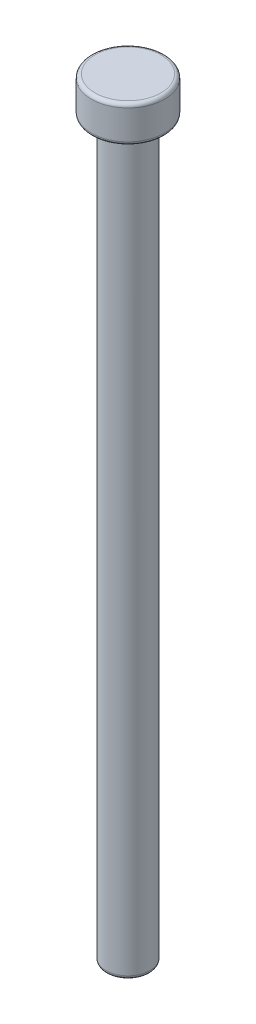
SolidWorks part; units mm, degrees
ref_plane "前基準面" through (0, 0, 0) normal (0, 0, 1) x (1, 0, 0)
ref_plane "上基準面" through (0, 0, 0) normal (0, 1, 0) x (1, 0, 0)
ref_plane "右基準面" through (0, 0, 0) normal (1, 0, 0) x (0, 0, -1)
sketch "草圖1" plane through (0, 0, 0) normal (0, 1, 0) x (1, 0, 0)
  circle A0 centre (0, 0) radius 5
  dimension "D1" = 10
extrude "伸長1" add sketch "草圖1" along normal blind 5
sketch "草圖2" plane through (0, 0, 0) normal (0, -1, 0) x (1, 0, 0)
  circle A0 centre (0, 0) radius 3
  dimension "D1" = 6
extrude "伸長2" add sketch "草圖2" along normal blind 100
fillet "圓角1" radius 0.5 4 edges at (0, -100, -3) (0, 0, 3) (0, 0, 5) (0, 5, 5)
